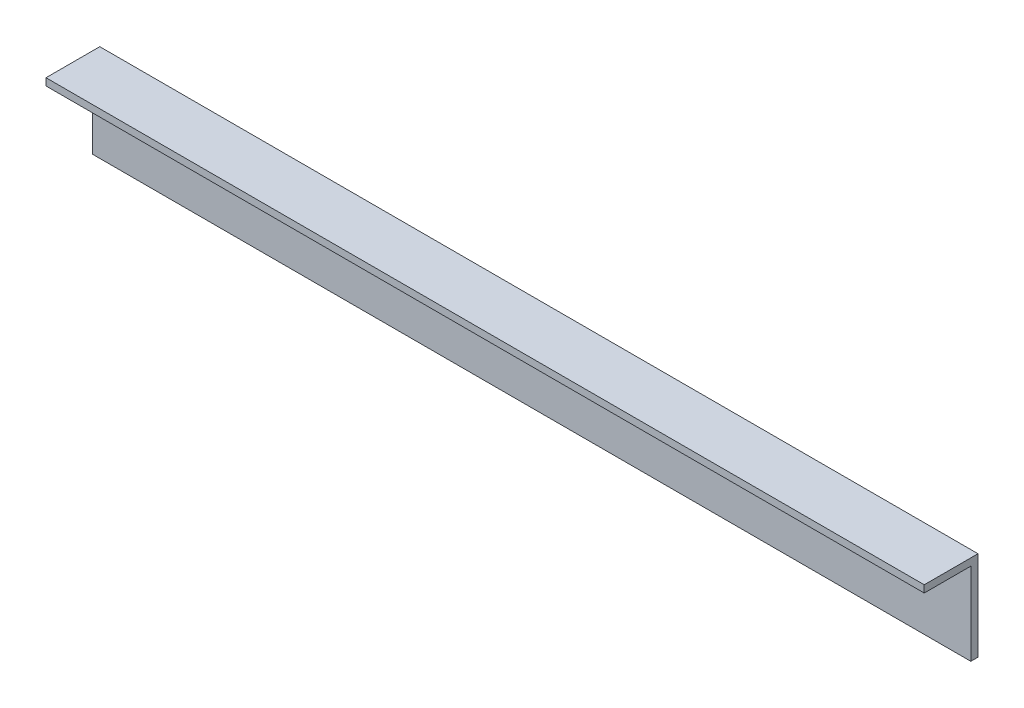
SolidWorks part; units mm, degrees
ref_plane "前视" through (0, 0, 0) normal (0, 0, 1) x (1, 0, 0)
ref_plane "上视" through (0, 0, 0) normal (0, 1, 0) x (1, 0, 0)
ref_plane "右视" through (0, 0, 0) normal (1, 0, 0) x (0, 0, -1)
sketch "草图1" plane through (0, 0, 0) normal (0, 0, 1) x (1, 0, 0)
  line L0 (0, 0) -> (0, 200.0571) construction
  line L1 (0, 200.0571) -> (0, 106) construction
  line L2 (210, 146) -> (953.1711, 146) construction
  line L3 (-980, 200) -> (980, 200)
  line L4 (-980, 200) -> (-980, 0)
  line L5 (-980, 0) -> (980, 0)
  line L6 (980, 200) -> (980, 0)
  line L9 (953.1711, 34) -> (210, 34) construction
  line L15 (0, 0) -> (330, 0) construction
  line L16 (0, 0) -> (1632.9772, 0) construction
  line L17 (-1004.6224, 106) -> (1007.8631, 106) construction
  line L20 (550, 175.3513) -> (550, 17.8164) construction
  line L21 (450, 293.2849) -> (450, -102.0826) construction
  line L22 (370, 293.2849) -> (370, -134.4898) construction
  line L23 (290, 293.2849) -> (290, -79.3976) construction
  line L24 (210, 293.2849) -> (210, -79.3976) construction
  line L25 (130, 293.2849) -> (130, -79.3976) construction
  line L26 (410, 320.2436) -> (410, -207.8775) construction
  dimension "D1" = 200
  dimension "D3" = 54
  dimension "D19" = 530
  dimension "D20" = 80
  dimension "D21" = 80
  dimension "D22" = 80
  dimension "D23" = 80
  dimension "D24" = 40
extrude "基体-拉伸" add sketch "草图1" along normal blind 16
sketch "草图2" plane through (0, 0, 16) normal (0, 0, 1) x (1, 0, 0)
  line L0 (0, 0) -> (0, 345.2694) construction
  line L1 (980, 0) -> (980, 200) construction
  line L2 (-980, 200) -> (980, 200)
  line L3 (-980, 200) -> (-980, 184)
  line L4 (-980, 184) -> (980, 184)
  line L5 (980, 200) -> (980, 184)
  dimension "D1" = 16
extrude "凸台-拉伸1" add sketch "草图2" along normal blind 104
